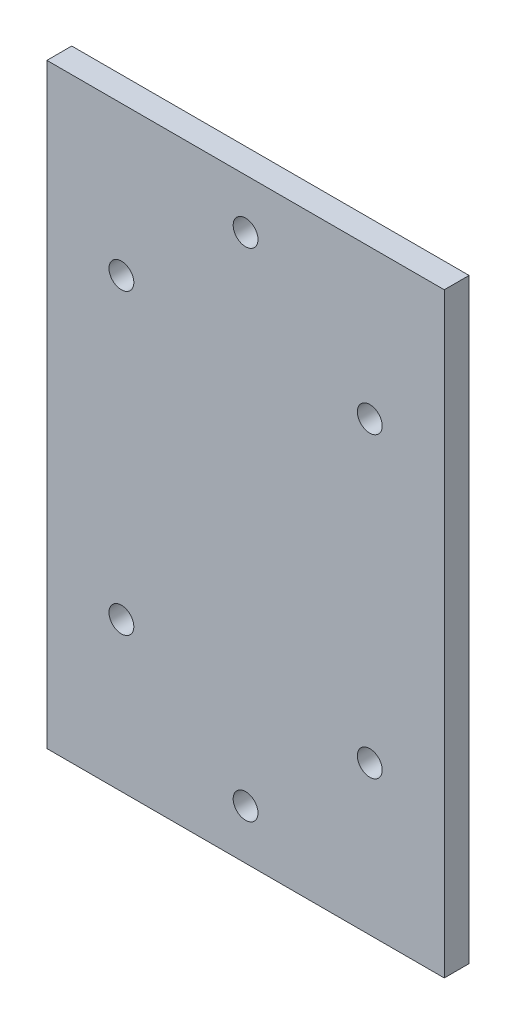
SolidWorks part; units mm, degrees
ref_plane "Front Plane" through (0, 0, 0) normal (0, 0, 1) x (1, 0, 0)
ref_plane "Top Plane" through (0, 0, 0) normal (0, 1, 0) x (1, 0, 0)
ref_plane "Right Plane" through (0, 0, 0) normal (1, 0, 0) x (0, 0, -1)
sketch "Sketch2" plane through (0, 0, 0) normal (0, 0, 1) x (1, 0, 0)
  line L0 (0, 0) -> (0, -15) construction
  line L1 (-20, -30) -> (20, -30)
  line L2 (-20, -30) -> (-20, 30)
  line L3 (-20, 30) -> (20, 30)
  line L4 (20, -30) -> (20, 30)
  line L5 (-20, -30) -> (20, 30) construction
  line L6 (-20, 30) -> (20, -30) construction
  line L7 (0, -15) -> (12.5, -15) construction
  line L8 (0, 0) -> (0, -25) construction
  line L9 (0, 0) -> (20, 0) construction
  line L10 (0, 15) -> (12.5, 15) construction
  line L11 (-20, 30) -> (20, 30)
  circle A0 centre (12.5, -15) radius 1.25
  circle A1 centre (-12.5, -15) radius 1.25
  circle A2 centre (0, -25) radius 1.25
  circle A3 centre (0, 25) radius 1.25
  circle A4 centre (-12.5, 15) radius 1.25
  circle A5 centre (12.5, 15) radius 1.25
  point P0 (0, 0)
  dimension "D3" = 2.5
  dimension "D6" = 2.5
  dimension "D1" = 40
  dimension "D2" = 60
  dimension "D4" = 15
  dimension "D5" = 12.5
  dimension "D7" = 25
extrude "Boss-Extrude2" add sketch "Sketch2" along normal blind 2.5 contours L1 L4 L3 L2 A3 A2 A0 A1 A4 A5
sketch "Sketch3" plane through (0, 0, 2.5) normal (0, 0, 1) x (1, 0, 0)
  line L0 (0, 0) -> (0, -40.08) construction
  circle A0 centre (0, -40.08) radius 6.7979
